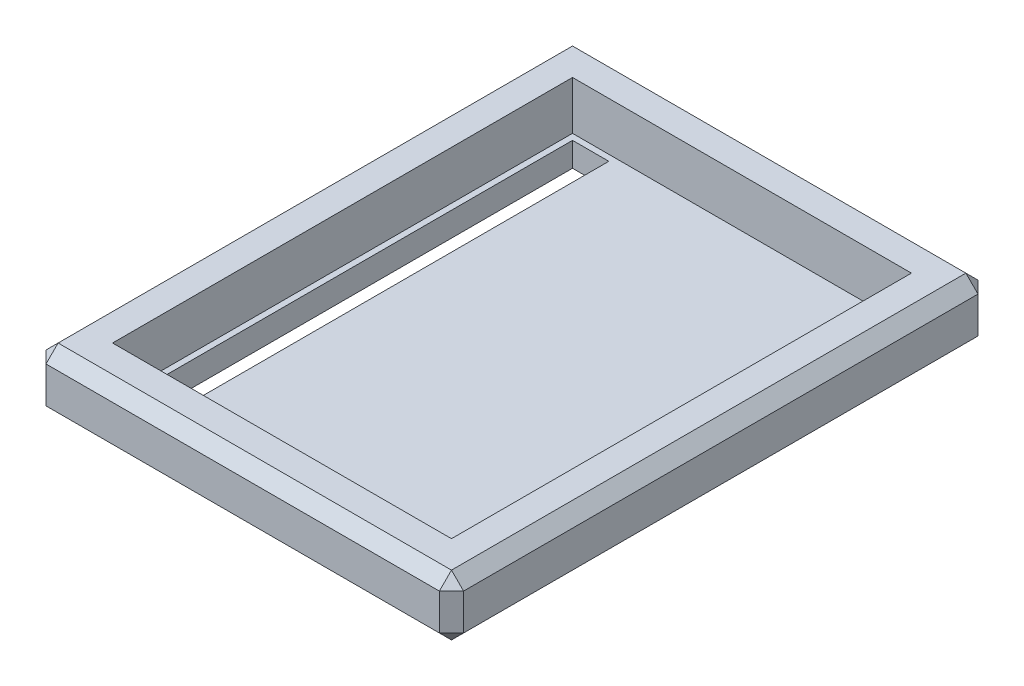
SolidWorks part; units mm, degrees
ref_plane "Front Plane" through (0, 0, 0) normal (0, 0, 1) x (1, 0, 0)
ref_plane "Top Plane" through (0, 0, 0) normal (0, 1, 0) x (1, 0, 0)
ref_plane "Right Plane" through (0, 0, 0) normal (1, 0, 0) x (0, 0, -1)
sketch "Sketch1" plane through (0, 0, 0) normal (0, 1, 0) x (1, 0, 0)
  line L0 (-355.6, 0) -> (0, 0) construction
  line L1 (-355.6, -482.6) -> (355.6, -482.6)
  line L2 (-355.6, -482.6) -> (-355.6, 482.6)
  line L3 (-355.6, 482.6) -> (355.6, 482.6)
  line L4 (355.6, -482.6) -> (355.6, 482.6)
  line L5 (0, 0) -> (355.6, 0) construction
  line L6 (0, 0) -> (0, 482.6) construction
  line L7 (0, 0) -> (0, -482.6) construction
  line L9 (-342.9, 469.9) -> (-266.7, 469.9)
  line L10 (-342.9, 469.9) -> (-342.9, -469.9)
  line L11 (-342.9, -469.9) -> (-266.7, -469.9)
  line L12 (-266.7, 469.9) -> (-266.7, -469.9)
  line L13 (342.9, 469.9) -> (266.7, 469.9)
  line L14 (342.9, 469.9) -> (342.9, -469.9)
  line L15 (342.9, -469.9) -> (266.7, -469.9)
  line L16 (266.7, 469.9) -> (266.7, -469.9)
  dimension "D1" = 711.2
  dimension "D2" = 965.2
  dimension "D3" = 12.7
  dimension "D4" = 12.7
  dimension "D5" = 12.7
  dimension "D6" = 12.7
  dimension "D7" = 12.7
  dimension "D8" = 12.7
  dimension "D9" = 76.2
  dimension "D10" = 76.2
extrude "Boss-Extrude1" add sketch "Sketch1" along normal blind 50.8
sketch "Sketch2" plane through (0, 0, 482.6) normal (0, 0, 1) x (1, 0, 0)
  line L0 (-355.6, 0) -> (355.6, 0) construction
  line L1 (-355.6, 25.4) -> (355.6, 25.4)
  line L2 (-355.6, 25.4) -> (-355.6, 152.4)
  line L3 (-355.6, 152.4) -> (355.6, 152.4)
  line L4 (355.6, 25.4) -> (355.6, 152.4)
  line L5 (-355.6, 50.8) -> (-355.6, 0) construction
  line L6 (355.6, 50.8) -> (355.6, 0) construction
  dimension "D1" = 127
  dimension "D2" = 25.4
extrude "Boss-Extrude2" add sketch "Sketch2" along normal blind 82.55
sketch "Sketch3" plane through (0, 0, -482.6) normal (0, 0, -1) x (-1, 0, 0)
  line L0 (-355.6, 50.8) -> (-355.6, 0) construction
  line L1 (-355.6, 25.4) -> (355.6, 25.4)
  line L2 (-355.6, 25.4) -> (-355.6, 152.4)
  line L3 (-355.6, 152.4) -> (355.6, 152.4)
  line L4 (355.6, 25.4) -> (355.6, 152.4)
  line L5 (355.6, 50.8) -> (355.6, 0) construction
  line L6 (-355.6, 0) -> (355.6, 0) construction
  dimension "D1" = 127
  dimension "D2" = 25.4
extrude "Boss-Extrude3" add sketch "Sketch3" along normal blind 82.55
sketch "Sketch4" plane through (355.6, 0, 0) normal (1, 0, 0) x (0, 0, -1)
  line L1 (-565.15, 25.4) -> (565.15, 25.4)
  line L2 (-565.15, 25.4) -> (-565.15, 152.4)
  line L3 (-565.15, 152.4) -> (565.15, 152.4)
  line L4 (565.15, 25.4) -> (565.15, 152.4)
extrude "Boss-Extrude4" add sketch "Sketch4" along normal blind 82.55
sketch "Sketch5" plane through (-355.6, 0, 0) normal (-1, 0, 0) x (0, 0, 1)
  line L1 (-565.15, 25.4) -> (565.15, 25.4)
  line L2 (-565.15, 25.4) -> (-565.15, 152.4)
  line L3 (-565.15, 152.4) -> (565.15, 152.4)
  line L4 (565.15, 25.4) -> (565.15, 152.4)
extrude "Boss-Extrude5" add sketch "Sketch5" along normal blind 82.55
chamfer "Chamfer1" distance 25.4 distance2 25.4 12 edges at (0, 25.4, 565.15) (0, 152.4, 565.15) (438.15, 25.4, 0) (438.15, 88.9, 565.15) (438.15, 152.4, 0) (0, 25.4, -565.15) (-438.15, 25.4, 0) (-438.15, 88.9, 565.15) (-438.15, 152.4, 0) (-438.15, 88.9, -565.15) (0, 152.4, -565.15) (438.15, 88.9, -565.15)
